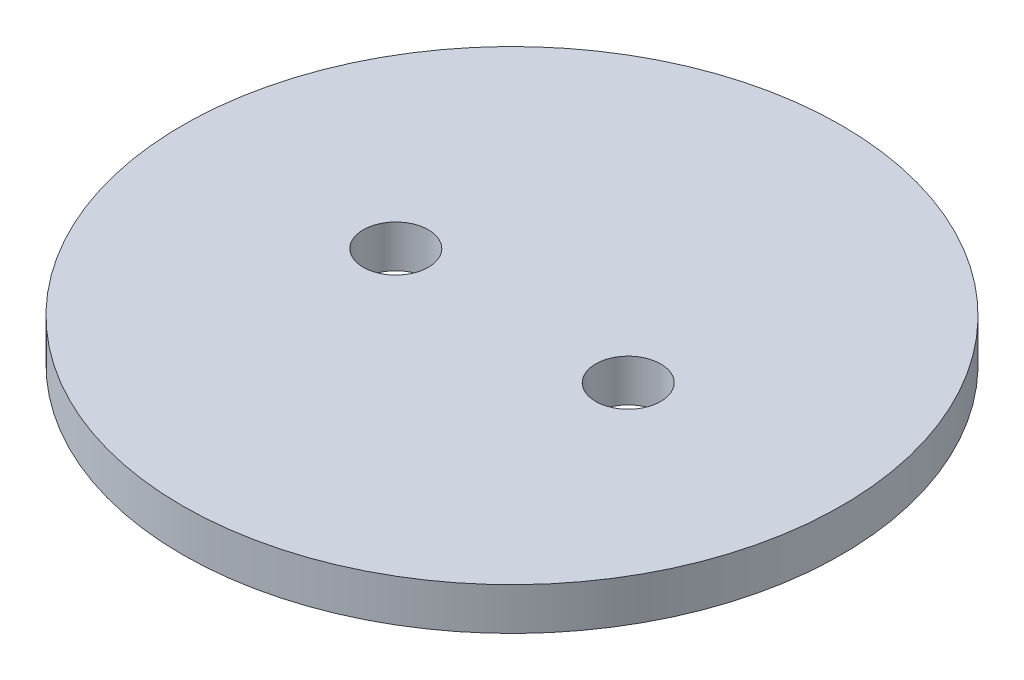
SolidWorks part; units mm, degrees
material "Acrylic (Medium-high impact)"
ref_plane "Front Plane" through (0, 0, 0) normal (0, 0, 1) x (1, 0, 0)
ref_plane "Top Plane" through (0, 0, 0) normal (0, 1, 0) x (1, 0, 0)
ref_plane "Right Plane" through (0, 0, 0) normal (1, 0, 0) x (0, 0, -1)
sketch "Sketch1" plane through (0, 0, 0) normal (0, 1, 0) x (1, 0, 0)
  circle A0 centre (0, 0) radius 49.53
  dimension "D1" = 99.06
extrude "Boss-Extrude1" add sketch "Sketch1" along normal blind 6.35
sketch "Sketch2" plane through (0, 6.35, 0) normal (0, 1, 0) x (1, 0, 0)
  line L0 (-49.1294, 0) -> (49.53, 0) construction
  circle A0 centre (0, 0) radius 49.53 construction
  circle A1 centre (-17.4625, 0) radius 4.8895
  circle A2 centre (17.4625, 0) radius 4.8895
  dimension "D3" = 9.779
  dimension "D1" = 34.925
  dimension "D2" = 17.4625
extrude "Cut-Extrude1" cut sketch "Sketch2" against normal through all
equation "\"D2@Sketch2\"=\"D1@Sketch2\"/2"
